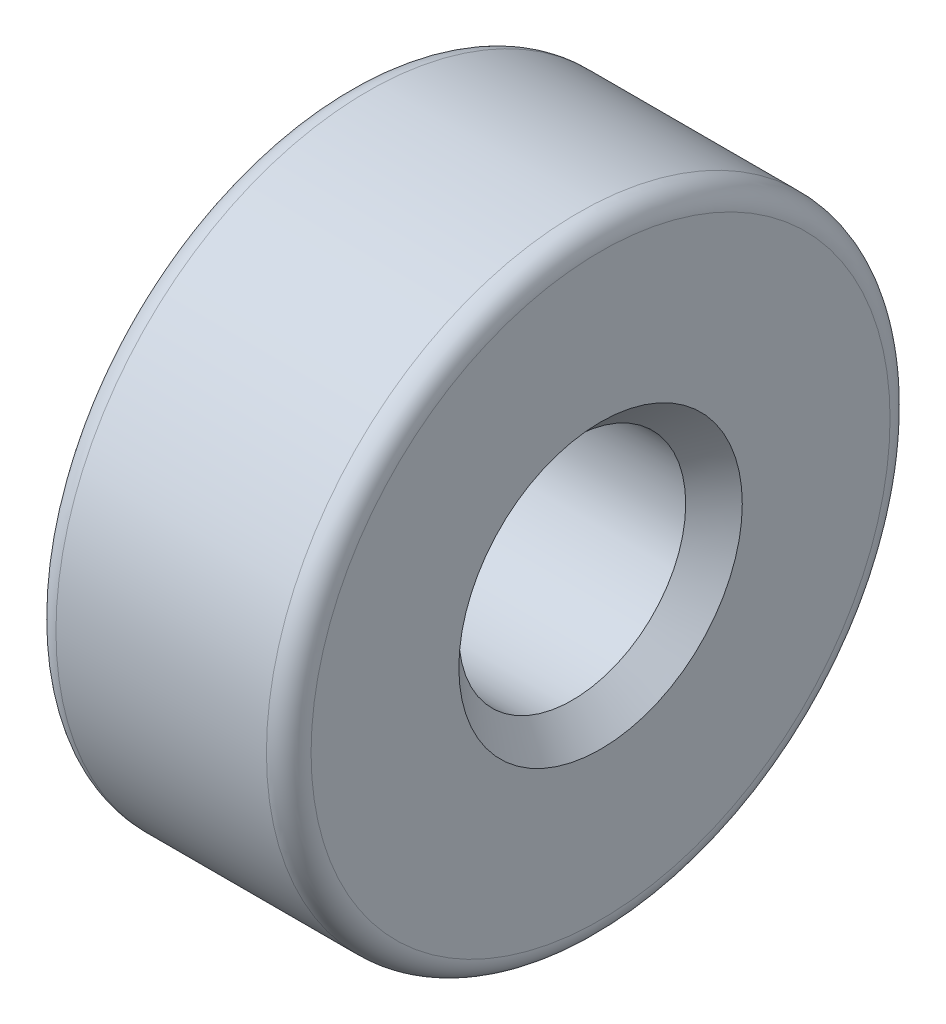
SolidWorks part; units mm, degrees
ref_plane "Front Plane" through (0, 0, 0) normal (0, 0, 1) x (1, 0, 0)
ref_plane "Top Plane" through (0, 0, 0) normal (0, 1, 0) x (1, 0, 0)
ref_plane "Right Plane" through (0, 0, 0) normal (1, 0, 0) x (0, 0, -1)
sketch "Sketch1" plane through (0, 0, 0) normal (0, 0, 1) x (1, 0, 0)
  line L0 (0, 0) -> (114.3, 0) construction
  line L3 (12.6714, 50.8286) -> (49.2146, 50.8286)
  line L5 (0, 63.5) -> (12.6714, 50.8286)
  line L7 (114.3, 63.5) -> (101.6286, 50.8286)
  line L9 (96.2945, 50.8286) -> (101.6286, 50.8286)
  line L10 (0, 63.5) -> (0, 139.7)
  line L11 (0, 139.7) -> (114.3, 139.7)
  line L12 (114.3, 139.7) -> (114.3, 63.5)
  line L13 (49.2146, 50.8286) -> (96.2945, 50.8286)
  dimension "D1" = 76.2
  dimension "D2" = 114.3
revolve "Revolve1" add sketch "Sketch1" angle 360 about L0
fillet "Fillet1" radius 10 2 edges at (114.3, 0, 139.7) (0, 0, 139.7)
